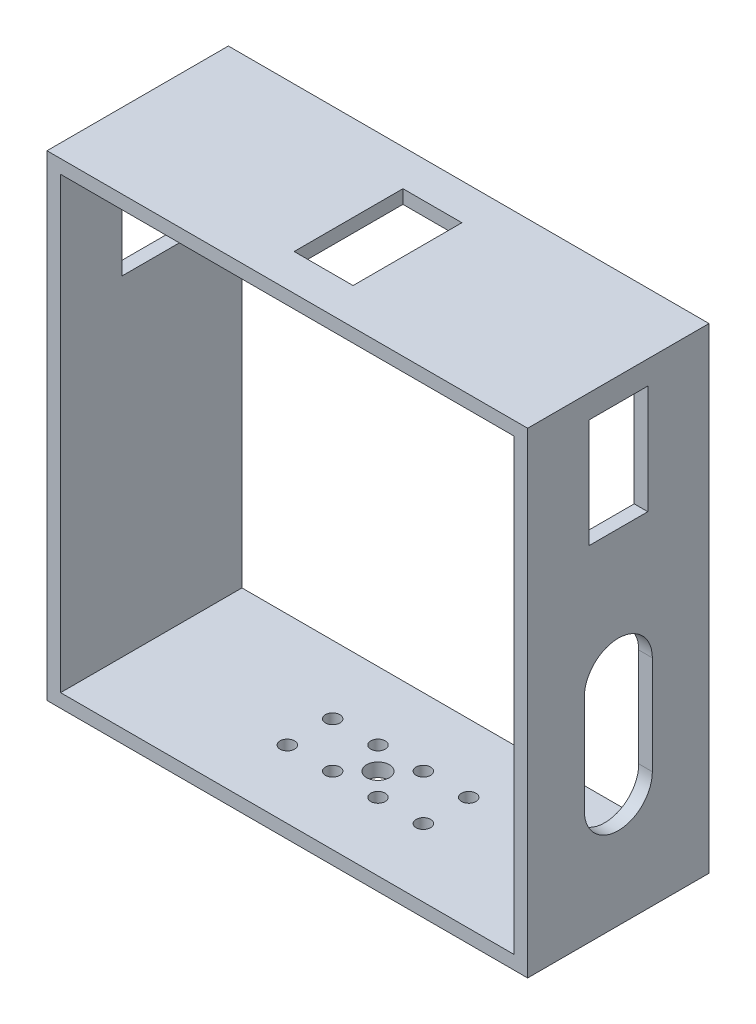
SolidWorks part; units mm, degrees
ref_plane "前视基准面" through (0, 0, 0) normal (0, 0, 1) x (1, 0, 0)
ref_plane "上视基准面" through (0, 0, 0) normal (0, 1, 0) x (1, 0, 0)
ref_plane "右视基准面" through (0, 0, 0) normal (1, 0, 0) x (0, 0, -1)
other "Configuration Table"
sketch "草图1" plane through (0, 0, 0) normal (0, 0, 1) x (1, 0, 0)
  line L0 (146.0665, 0) -> (-146.0665, 0) construction
  line L1 (0, -83.0601) -> (0, 83.0601) construction
  line L2 (28, 61.896) -> (-28, 61.896) construction
  line L3 (-28, 61.896) -> (-28, -91.7584) construction
  line L4 (28, 61.896) -> (28, -90.2615) construction
  line L15 (-53, 0) -> (-53, 105)
  line L16 (-53, 105) -> (53, 105)
  line L17 (53, 0) -> (53, 105)
  line L20 (-53, 0) -> (53, 0)
  point P0 (-28, 0)
  point P4 (0, 0)
  point P8 (0, 0)
  point P11 (0, 61.896)
  point P14 (28, 0)
  dimension "D1" = 106
extrude "凸台-拉伸1" add sketch "草图1" along normal blind 40
sketch "草图3" plane through (0, 0, 0) normal (0, 0, -1) x (-1, 0, 0)
  line L0 (0, 0) -> (0, 165.1711) construction
  line L1 (0, 0) -> (-121.8649, 0) construction
  line L2 (-50, 105) -> (-50, 102) construction
  line L3 (-53, 105) -> (53, 105) construction
  line L4 (-53, 0) -> (-53, 105) construction
  line L5 (-23.3554, 105) -> (-23.3554, 0) construction
  line L6 (-23.3554, 52.5) -> (-117.2398, 52.5) construction
  line L7 (50, 105) -> (50, 102) construction
  line L8 (50, 0) -> (50, 3) construction
  line L9 (-50, 0) -> (-50, 3) construction
  line L10 (53, 0) -> (-53, 0) construction
  line L11 (-50, 102) -> (50, 102)
  line L12 (-50, 102) -> (-50, 3)
  line L13 (-50, 3) -> (50, 3)
  line L14 (50, 102) -> (50, 3)
  dimension "D1" = 3
  dimension "D2" = 3
sketch "草图8" plane through (-53, 0, 0) normal (-1, 0, 0) x (0, 0, 1)
  line L0 (22.5, 130.575) -> (17.5, 130.575) construction
  line L1 (20, 105) -> (20, 141) construction
  line L2 (20, 141) -> (20, 132.5) construction
  line L6 (20, 141) -> (20, 113) construction
  line L8 (17.5, 130.575) -> (17.5, 127.601) construction
  line L9 (22.5, 130.575) -> (22.5, 127.601) construction
  line L10 (22.5, 127.601) -> (17.5, 127.601) construction
  line L11 (40, 105) -> (0, 105) construction
  circle A7 centre (20, 141) radius 1
  circle A8 centre (20, 113) radius 1
  circle A9 centre (20, 132.5) radius 5.5 construction
  arc A10 (17.5, 127.601) -> (22.5, 127.601) centre (20, 132.5) cw
  arc A11 (17.5, 127.601) -> (22.5, 127.601) centre (20, 127.1286) ccw
  point P10 (20, 130.575)
extrude "切除-拉伸1" cut sketch "草图3" against normal through all both and the other way through all
sketch "草图7" plane through (0, 0, 0) normal (0, -1, 0) x (1, 0, 0)
  line L0 (-53, 20) -> (53, 20) construction
  line L1 (-53, 40) -> (-53, 0) construction
  line L2 (53, 40) -> (53, 0) construction
  line L3 (0, 40) -> (0, 0) construction
  line L4 (-53, 40) -> (53, 40) construction
  line L5 (5, 25) -> (15, 25) construction
  line L6 (-5, 15) -> (5, 15) construction
  line L7 (-5, 15) -> (-5, 25) construction
  line L8 (-5, 25) -> (5, 25) construction
  line L9 (5, 15) -> (5, 25) construction
  line L10 (0, 25) -> (0, 15) construction
  line L11 (-5, 20) -> (5, 20) construction
  circle A0 centre (0, 20) radius 2.5
  circle A1 centre (5, 25) radius 1.6
  circle A2 centre (5, 15) radius 1.6
  circle A3 centre (-5, 15) radius 1.6
  circle A4 centre (-5, 25) radius 1.6
  circle A5 centre (15, 25) radius 1.6
  circle A6 centre (-15, 25) radius 1.6
  circle A7 centre (15, 15) radius 1.6
  circle A8 centre (-15, 15) radius 1.6
extrude "切除-拉伸3" cut sketch "草图7" against normal blind 3 and the other way blind 1
sketch "草图6" plane through (0, 105, 0) normal (0, 1, 0) x (1, 0, 0)
  line L0 (0, 0) -> (0, -40) construction
  line L1 (-53, -20) -> (53, -20) construction
  line L2 (6.5, -32) -> (6.5, -8)
  line L3 (53, -40) -> (53, 0) construction
  line L4 (53, -40) -> (-53, -40) construction
  line L9 (0, -16.2741) -> (0, -37.4626) construction
  line L10 (-6.5, -32) -> (-6.5, -8)
  line L11 (-6.5, -8) -> (6.5, -8)
  line L13 (6.5, -32.5) -> (6.5, -7.5) construction
  line L15 (-6.5, -32.5) -> (-6.5, -7.5) construction
  line L16 (0, -7.5) -> (0, -32.5) construction
  line L17 (6.5, -20) -> (-6.5, -20) construction
  line L18 (-6.5, -32) -> (6.5, -32)
  point P5 (0, -20)
  point P9 (6.5, -20)
  point P19 (-6.5, -20)
extrude "切除-拉伸4" cut sketch "草图6" against normal up to next and the other way through all
sketch "草图10" plane through (-53, 0, 0) normal (-1, 0, 0) x (0, 0, 1)
  line L0 (20, 0) -> (20, 160.7067) construction
  line L1 (40, 0) -> (0, 0) construction
  line L2 (35.1632, 99.807) -> (4.8368, 99.807) construction
  line L3 (20, 101.807) -> (29.1345, 101.807) construction
  line L6 (26.5, 99.807) -> (13.5, 99.807)
  line L8 (20, 99.807) -> (20, 74.807) construction
  line L9 (26.5, 87.307) -> (13.5, 87.307) construction
  line L10 (13.5, 99.807) -> (13.5, 75.807)
  line L11 (13.5, 75.807) -> (26.5, 75.807)
  line L12 (26.5, 75.807) -> (26.5, 99.807)
  point P4 (20, 87.307)
  point P7 (20, 99.807)
  dimension "D1" = 24
  dimension "D2" = 2
extrude "切除-拉伸5" cut sketch "草图10" against normal through all both and the other way through all
sketch "草图12" plane through (53, 0, 0) normal (1, 0, 0) x (0, 0, -1)
  line L0 (-20, 0) -> (-20, 69.2078) construction
  line L1 (-40, 0) -> (0, 0) construction
  line L2 (-20, 25.65) -> (-20, 47.3985) construction
  line L3 (-27.5, 25.65) -> (-27.5, 47.3985)
  line L4 (-12.5, 25.65) -> (-12.5, 47.3985)
  arc A0 (-27.5, 25.65) -> (-12.5, 25.65) centre (-20, 25.65) ccw
  arc A1 (-12.5, 47.3985) -> (-27.5, 47.3985) centre (-20, 47.3985) ccw
  point P6 (-20, 36.5242)
  dimension "D1" = 15
extrude "切除-拉伸6" cut sketch "草图12" against normal up to next and the other way through all
